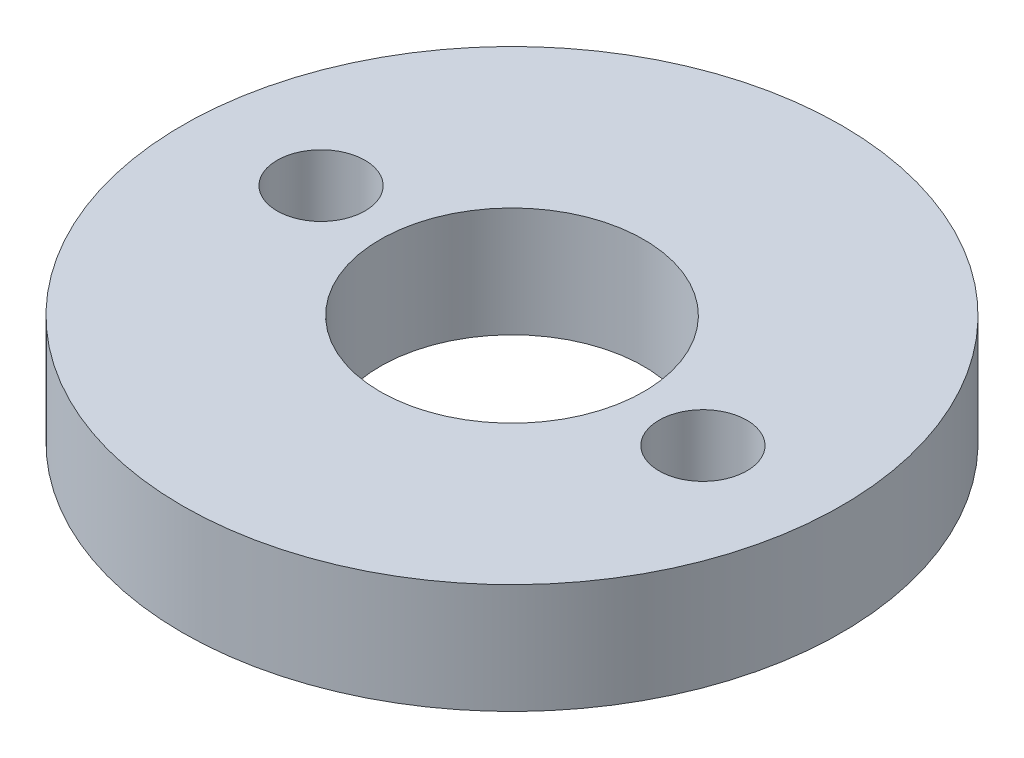
SolidWorks part; units mm, degrees
ref_plane "Front Plane" through (0, 0, 0) normal (0, 0, 1) x (1, 0, 0)
ref_plane "Top Plane" through (0, 0, 0) normal (0, 1, 0) x (1, 0, 0)
ref_plane "Right Plane" through (0, 0, 0) normal (1, 0, 0) x (0, 0, -1)
sketch "Sketch1" plane through (0, 0, 0) normal (0, 1, 0) x (1, 0, 0)
  circle A0 centre (0, 0) radius 15
  circle A1 centre (0, 0) radius 6
extrude "Boss-Extrude1" add sketch "Sketch1" along normal blind 5
sketch "Sketch2" plane through (0, 0, 0) normal (0, -1, 0) x (1, 0, 0)
  circle A0 centre (-9.4681, -0.7774) radius 2
  circle A1 centre (9.4681, 0.7774) radius 2
extrude "Cut-Extrude1" cut sketch "Sketch2" against normal through all
